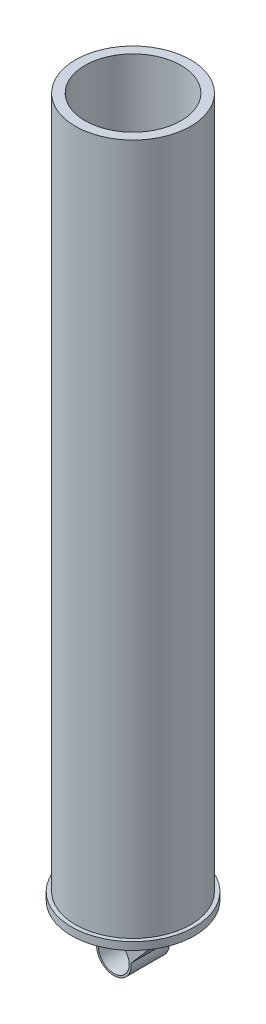
SolidWorks part; units mm, degrees
ref_plane "Front Plane" through (0, 0, 0) normal (0, 0, 1) x (1, 0, 0)
ref_plane "Top Plane" through (0, 0, 0) normal (0, 1, 0) x (1, 0, 0)
ref_plane "Right Plane" through (0, 0, 0) normal (1, 0, 0) x (0, 0, -1)
sketch "Sketch1" plane through (0, 0, 0) normal (0, 1, 0) x (1, 0, 0)
  circle A0 centre (0, 0) radius 150
  circle A1 centre (0, 0) radius 125
  dimension "D1" = 300
  dimension "D2" = 250
extrude "Boss-Extrude1" add sketch "Sketch1" along normal blind 1800
sketch "Sketch2" plane through (0, 0, 0) normal (0, -1, 0) x (1, 0, 0)
  circle A0 centre (0, 0) radius 160
  dimension "D1" = 320
extrude "Boss-Extrude2" add sketch "Sketch2" along normal blind 20
sketch "Sketch4" plane through (0, 0, 0) normal (0, 0, 1) x (1, 0, 0)
  line L0 (-40, -119.7913) -> (-123.819, -20)
  line L1 (-160, -20) -> (160, -20) construction
  line L2 (40, -119.7913) -> (126.4699, -20)
  line L3 (-123.819, -20) -> (126.4699, -20)
  circle A0 centre (0, -119.7913) radius 40
  circle A1 centre (0, -119.7913) radius 45
  dimension "D1" = 80
  dimension "D2" = 90
extrude "Boss-Extrude3" add sketch "Sketch4" along normal mid plane 100 contours L0 A1 L2 A0 | L2 A1 L0 A0 | A1 L2 L3 L0
